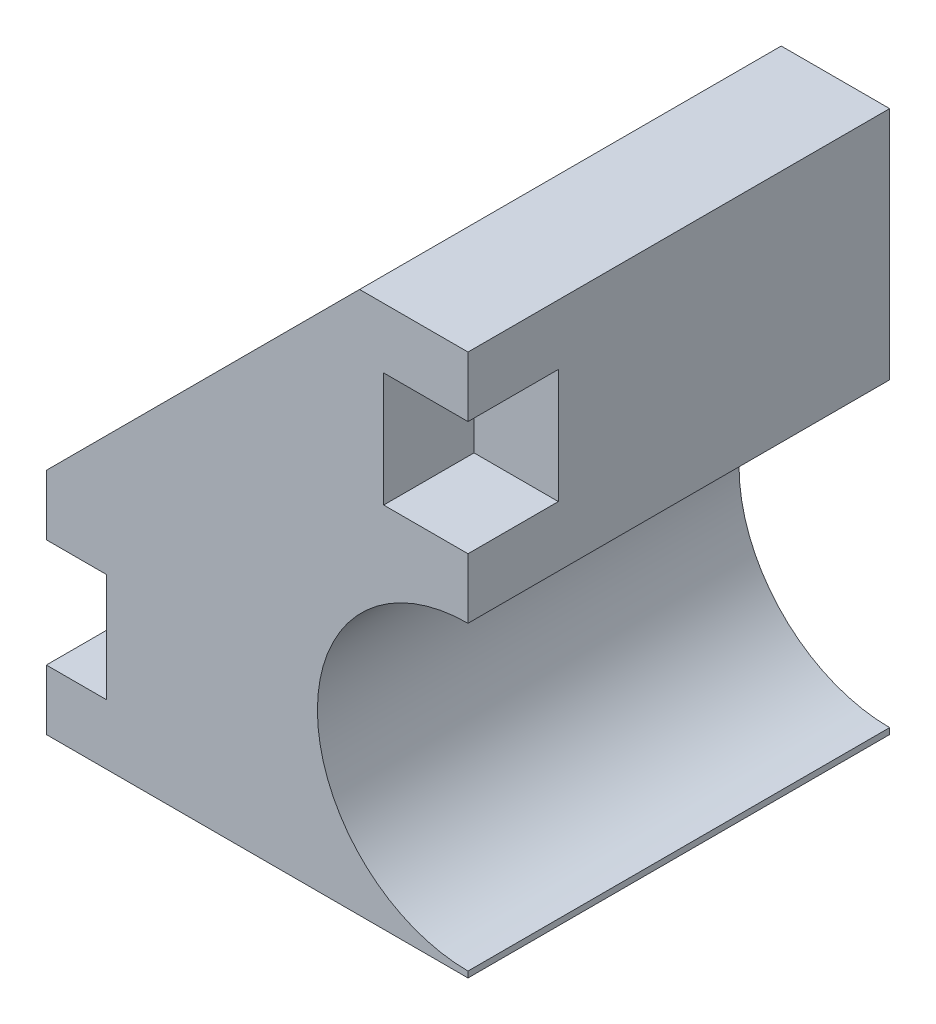
SolidWorks part; units mm, degrees
ref_plane "Front Plane" through (0, 0, 0) normal (0, 0, 1) x (1, 0, 0)
ref_plane "Top Plane" through (0, 0, 0) normal (0, 1, 0) x (1, 0, 0)
ref_plane "Right Plane" through (0, 0, 0) normal (1, 0, 0) x (0, 0, -1)
sketch "Sketch2" plane through (0, 0, 0) normal (0, 0, 1) x (1, 0, 0)
  line L0 (0, 0) -> (-35, 0)
  line L2 (0, 45) -> (0, 25.5)
  line L3 (0, 0.5) -> (0, 0)
  line L4 (-35, 19) -> (-35, 0)
  line L5 (0, 45) -> (-9, 45)
  line L6 (-9, 45) -> (-35, 19)
  arc A0 (0, 25.5) -> (0, 0.5) centre (0, 13) ccw
  dimension "D2" = 12.5
  dimension "D1" = 45
  dimension "D3" = 45
  dimension "D4" = 0.5
  dimension "D5" = 35
  dimension "D6" = 9
extrude "Boss-Extrude1" add sketch "Sketch2" along normal blind 150
sketch "Sketch3" plane through (0, 0, 0) normal (0, -1, 0) x (1, 0, 0)
  line L0 (-35, 150) -> (-35, 0) construction
  line L1 (-35, 115) -> (0, 115)
  line L2 (-35, 115) -> (-35, 35)
  line L3 (-35, 35) -> (0, 35)
  line L4 (0, 115) -> (0, 35)
  line L5 (-35, 150) -> (0, 150) construction
  line L6 (-35, 0) -> (0, 0) construction
  line L8 (0, 150) -> (0, 0) construction
  dimension "D1" = 35
  dimension "D2" = 35
  dimension "D3" = 0
extrude "Cut-Extrude1" cut sketch "Sketch3" against normal blind 150
sketch "Sketch5" plane through (0, 0, 0) normal (1, 0, 0) x (0, 0, -1)
  line L0 (-115, 45) -> (-115, 25.5) construction
  line L1 (-115, 40) -> (-122.5, 40)
  line L2 (-115, 40) -> (-115, 30.5)
  line L3 (-115, 30.5) -> (-122.5, 30.5)
  line L4 (-122.5, 40) -> (-122.5, 30.5)
  line L5 (-35, 45) -> (-35, 25.5) construction
  line L6 (-35, 40) -> (-27.5, 40)
  line L7 (-35, 40) -> (-35, 30.5)
  line L8 (-35, 30.5) -> (-27.5, 30.5)
  line L9 (-27.5, 40) -> (-27.5, 30.5)
  line L10 (-150, 45) -> (-115, 45) construction
  line L11 (-35, 45) -> (0, 45) construction
  dimension "D1" = 9.5
  dimension "D2" = 9.5
  dimension "D3" = 5
  dimension "D4" = 5
  dimension "D5" = 7.5
  dimension "D6" = 7.5
extrude "Cut-Extrude3" cut sketch "Sketch5" against normal blind 7
sketch "Sketch6" plane through (-35, 0, 0) normal (-1, 0, 0) x (0, 0, 1)
  line L0 (35, 19) -> (35, 0) construction
  line L1 (35, 14) -> (27.5, 14)
  line L2 (35, 14) -> (35, 5)
  line L3 (35, 5) -> (27.5, 5)
  line L4 (27.5, 14) -> (27.5, 5)
  line L5 (115, 19) -> (115, 0) construction
  line L6 (115, 14) -> (122.5, 14)
  line L7 (115, 14) -> (115, 5)
  line L8 (115, 5) -> (122.5, 5)
  line L9 (122.5, 14) -> (122.5, 5)
  line L10 (35, 0) -> (0, 0) construction
  line L11 (35, 19) -> (0, 19) construction
  line L12 (150, 19) -> (115, 19) construction
  line L13 (150, 0) -> (115, 0) construction
  dimension "D1" = 7.5
  dimension "D2" = 7.5
  dimension "D3" = 5
  dimension "D4" = 5
  dimension "D5" = 5
  dimension "D6" = 5
extrude "Cut-Extrude4" cut sketch "Sketch6" against normal blind 5
sketch "Sketch7" plane through (-35, 0, 0) normal (-1, 0, 0) x (0, 0, 1)
  line L1 (96.0897, 60.3006) -> (162.1289, 60.3006)
  line L2 (96.0897, 60.3006) -> (96.0897, -19.2325)
  line L3 (96.0897, -19.2325) -> (162.1289, -19.2325)
  line L4 (162.1289, 60.3006) -> (162.1289, -19.2325)
extrude "Cut-Extrude5" cut sketch "Sketch7" against normal blind 70
